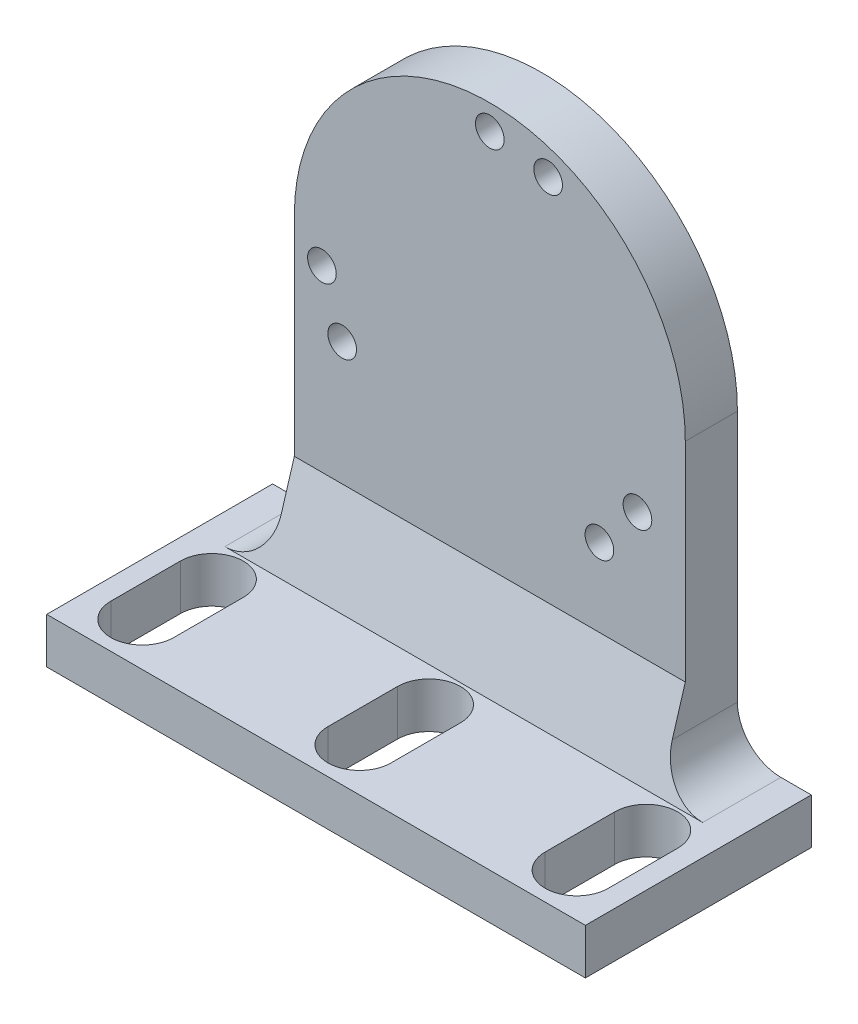
SolidWorks part; units mm, degrees
ref_plane "정면" through (0, 0, 0) normal (0, 0, 1) x (1, 0, 0)
ref_plane "윗면" through (0, 0, 0) normal (0, 1, 0) x (1, 0, 0)
ref_plane "우측면" through (0, 0, 0) normal (1, 0, 0) x (0, 0, -1)
sketch "스케치1" plane through (0, 0, 0) normal (0, 0, 1) x (1, 0, 0)
  line L0 (43.8545, -7.7327) -> (-43.8545, 7.7327) construction
  line L1 (-7.0983, -40.2563) -> (7.0983, 40.2563) construction
  line L2 (-32.3773, 0) -> (32.3773, 0) construction
  line L3 (0, -34.2182) -> (0, 34.2182) construction
  line L4 (6.7111, 18.4386) -> (0, 0) construction
  line L6 (-22.5, -34) -> (22.5, -34)
  line L7 (-22.5, -34) -> (-22.5, 0)
  line L8 (-22.5, 0) -> (22.5, 0) construction
  line L9 (22.5, -34) -> (22.5, 0)
  line L10 (-22.5, -34) -> (22.5, 0) construction
  line L11 (-22.5, 0) -> (22.5, -34) construction
  circle A0 centre (0, 0) radius 19.622 construction
  circle A1 centre (6.7111, 18.4386) radius 1.65
  circle A2 centre (0, 19.622) radius 1.65
  circle A3 centre (16.9932, -9.811) radius 1.65
  circle A4 centre (12.6128, -15.0313) radius 1.65
  circle A5 centre (-16.9932, -9.811) radius 1.65
  circle A6 centre (-19.3239, -3.4073) radius 1.65
  circle A7 centre (0, 0) radius 22.5 construction
  arc A8 (-22.5, 0) -> (22.5, 0) centre (0, 0) cw
  point P6 (0, 0)
  point P9 (0, 0)
  point P12 (0, 0)
  point P15 (0, 0)
  point P20 (0, -17)
  point P29 (0, 0)
  point P34 (43.7899, -8.0906)
  dimension "D1" = 39.244
  dimension "D3" = 3.3
  dimension "D6" = 45
  dimension "D2" = 10
  dimension "D4" = 10
  dimension "D7" = 45
  dimension "D8" = 34
  dimension "D5" = 3
extrude "보스-돌출1" add sketch "스케치1" along normal blind 6 contours A8 L7 L6 L9 A6 A3 A1 A2 A4 A5
sketch "스케치2" plane through (0, 0, 0) normal (0, 0, 1) x (1, 0, 0)
  line L0 (-22.5, -34) -> (22.5, -34) construction
  line L1 (31, -39.25) -> (-31, -39.25)
  line L2 (31, -39.25) -> (31, -34)
  line L3 (31, -34) -> (-31, -34)
  line L4 (-31, -39.25) -> (-31, -34)
  line L5 (31, -39.25) -> (-31, -34) construction
  line L6 (31, -34) -> (-31, -39.25) construction
  point P0 (0, -36.625)
  point P7 (0, 0)
  dimension "D1" = 5.25
  dimension "D2" = 62
extrude "보스-돌출2" add sketch "스케치2" along normal blind 26
sketch "스케치3" plane through (0, -34, 0) normal (0, 1, 0) x (1, 0, 0)
  line L0 (0, -21) -> (0, -13) construction
  line L1 (-3.625, -21) -> (-3.625, -13)
  line L2 (3.625, -21) -> (3.625, -13)
  line L3 (19.9881, -13) -> (-19.9881, -13) construction
  line L4 (25, -21) -> (25, -13) construction
  line L5 (21.375, -21) -> (21.375, -13)
  line L6 (28.625, -21) -> (28.625, -13)
  line L7 (-25, -21) -> (-25, -13) construction
  line L8 (-28.625, -21) -> (-28.625, -13)
  line L9 (-21.375, -21) -> (-21.375, -13)
  arc A0 (-3.625, -21) -> (3.625, -21) centre (0, -21) ccw
  arc A1 (3.625, -13) -> (-3.625, -13) centre (0, -13) ccw
  arc A2 (21.375, -21) -> (28.625, -21) centre (25, -21) ccw
  arc A3 (28.625, -13) -> (21.375, -13) centre (25, -13) ccw
  arc A4 (-28.625, -21) -> (-21.375, -21) centre (-25, -21) ccw
  arc A5 (-21.375, -13) -> (-28.625, -13) centre (-25, -13) ccw
  point P2 (0, -17)
  point P11 (0, -13)
  point P13 (25, -17)
  point P19 (-25, -17)
  point P25 (0, 0)
  dimension "D2" = 3.625
  dimension "D5" = 3.625
  dimension "D9" = 3.625
  dimension "D1" = 13
  dimension "D3" = 8
  dimension "D4" = 25
  dimension "D6" = 8
  dimension "D7" = 25
  dimension "D8" = 8
extrude "컷-돌출1" cut sketch "스케치3" against normal through all
sketch "스케치4" plane through (0, 0, 0) normal (1, 0, 0) x (0, 0, -1)
  line L0 (-6, -24) -> (-9, -34)
  line L1 (-6, -34) -> (-6, 0) construction
  line L2 (-26, -34) -> (0, -34) construction
  line L3 (-9, -34) -> (-6, -34)
  line L4 (-6, -34) -> (-6, -24)
  dimension "D1" = 3
  dimension "D2" = 10
extrude "보스-돌출3" add sketch "스케치4" along normal mid plane 45
fillet "필렛1" radius 5 2 edges at (-22.5, -34, 4.5) (22.5, -34, 4.5)
